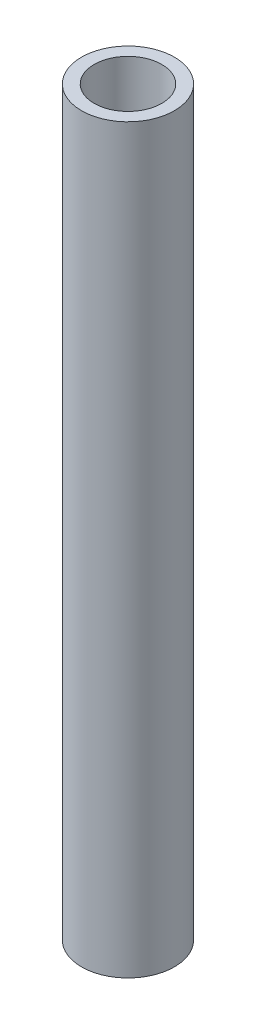
SolidWorks part; units mm, degrees
ref_plane "Front Plane" through (0, 0, 0) normal (0, 0, 1) x (1, 0, 0)
ref_plane "Top Plane" through (0, 0, 0) normal (0, 1, 0) x (1, 0, 0)
ref_plane "Right Plane" through (0, 0, 0) normal (1, 0, 0) x (0, 0, -1)
sketch "Sketch1" plane through (0, 0, 0) normal (0, 1, 0) x (1, 0, 0)
  circle A0 centre (0, 0) radius 24.3078
  circle A1 centre (0, 0) radius 33.401
extrude "Boss-Extrude1" add sketch "Sketch1" along normal mid plane 533.4
